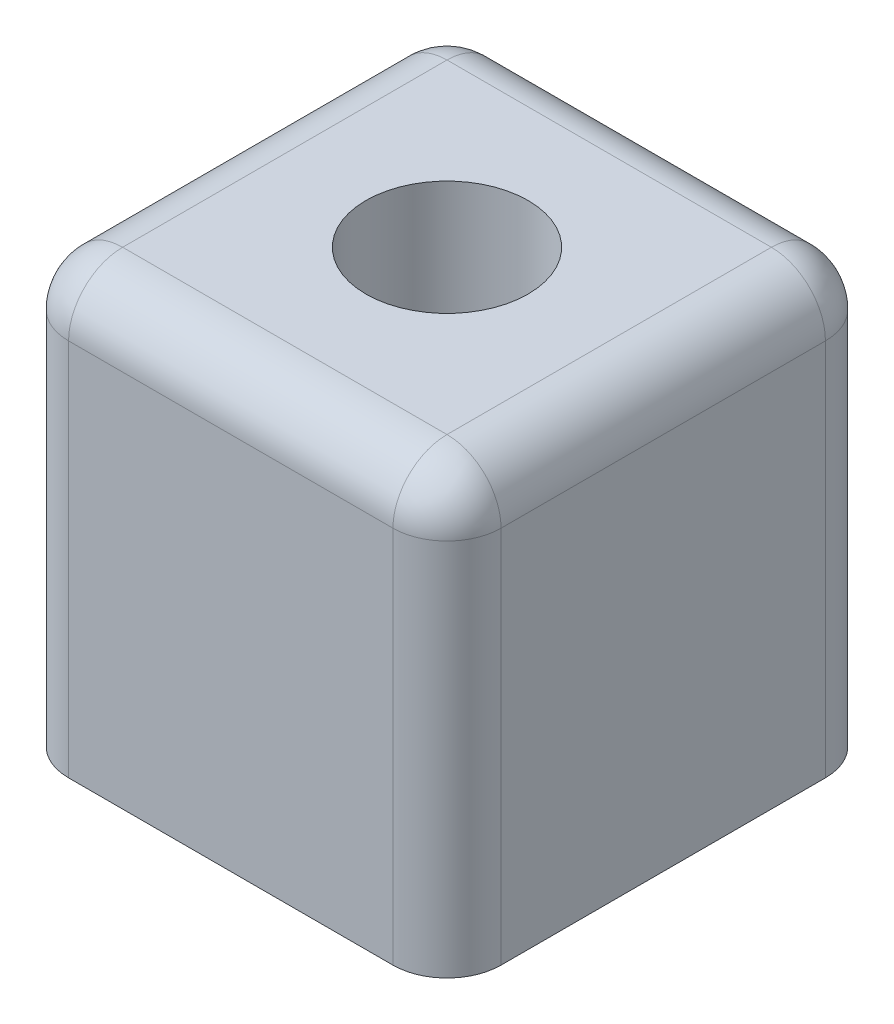
SolidWorks part; units mm, degrees
ref_plane "Ön Düzlem" through (0, 0, 0) normal (0, 0, 1) x (1, 0, 0)
ref_plane "Üst Düzlem" through (0, 0, 0) normal (0, 1, 0) x (1, 0, 0)
ref_plane "Sağ Düzlem" through (0, 0, 0) normal (1, 0, 0) x (0, 0, -1)
sketch "Çizim1" plane through (0, 0, 0) normal (0, 0, 1) x (1, 0, 0)
  line L1 (0, 0) -> (80, 0)
  line L2 (0, 0) -> (0, 80)
  line L3 (0, 80) -> (80, 80)
  line L4 (80, 0) -> (80, 80)
  dimension "D1" = 80
  dimension "D2" = 80
extrude "Yükseklik-Ekstrüzyon1" add sketch "Çizim1" along normal blind 80
sketch "Çizim2" plane through (0, 80, 0) normal (0, 1, 0) x (1, 0, 0)
  line L0 (0, -80) -> (80, 0) construction
  line L1 (80, 0) -> (80, -80) construction
  line L2 (80, -80) -> (0, 0) construction
  circle A0 centre (40, -40) radius 15
  dimension "D1" = 30
extrude "Kes-Ekstrüzyon1" cut sketch "Çizim2" against normal blind 50
fillet "Radyus1" radius 10 8 edges at (80, 80, 40) (40, 80, 80) (0, 80, 40) (40, 80, 0) (0, 40, 0) (80, 40, 0) (80, 40, 80) (0, 40, 80)
shell "İç Boşaltma1" thickness 3
